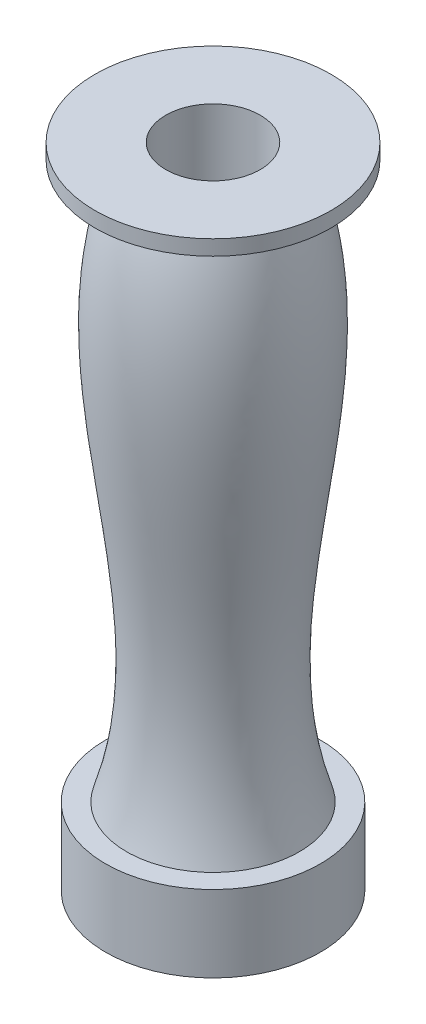
SolidWorks part; units mm, degrees
ref_plane "Front Plane" through (0, 0, 0) normal (0, 0, 1) x (1, 0, 0)
ref_plane "Top Plane" through (0, 0, 0) normal (0, 1, 0) x (1, 0, 0)
ref_plane "Right Plane" through (0, 0, 0) normal (1, 0, 0) x (0, 0, -1)
sketch "Sketch1" plane through (0, 0, 0) normal (0, 0, 1) x (1, 0, 0)
  line L0 (0, 150) -> (0, 0) construction
  line L1 (0, 0) -> (-20, 0)
  line L13 (0, 2.0629) -> (0, 0)
  line L14 (-15, 133.958) -> (-25, 133.958)
  line L15 (-25, 133.958) -> (-25, 137.1651)
  line L16 (-25, 137.1651) -> (-10, 137.1651)
  line L17 (-10, 137.1651) -> (-10, 12.132)
  line L18 (0, 2.0629) -> (-15.0654, 2.0629)
  line L19 (-15.0654, 2.0629) -> (-15.0654, 12.132)
  line L20 (-15.0654, 12.132) -> (-10, 12.132)
  line L21 (-18.3001, 16.2205) -> (-22.7338, 16.2205)
  line L22 (-22.7338, 16.2205) -> (-22.7338, 0)
  line L23 (-22.7338, 0) -> (-20, 0)
  spline S0 degree 3 poles (-18.3001, 16.2205) (-5.6705, 55.6735) (-30.1615, 94.4299) (-15, 133.958) knots 0 0 0 0 1 1 1 1
  dimension "D1" = 150
  dimension "D2" = 20
  dimension "D3" = 10
  dimension "D4" = 25
revolve "Revolve1" add sketch "Sketch1" angle 360 about L0
